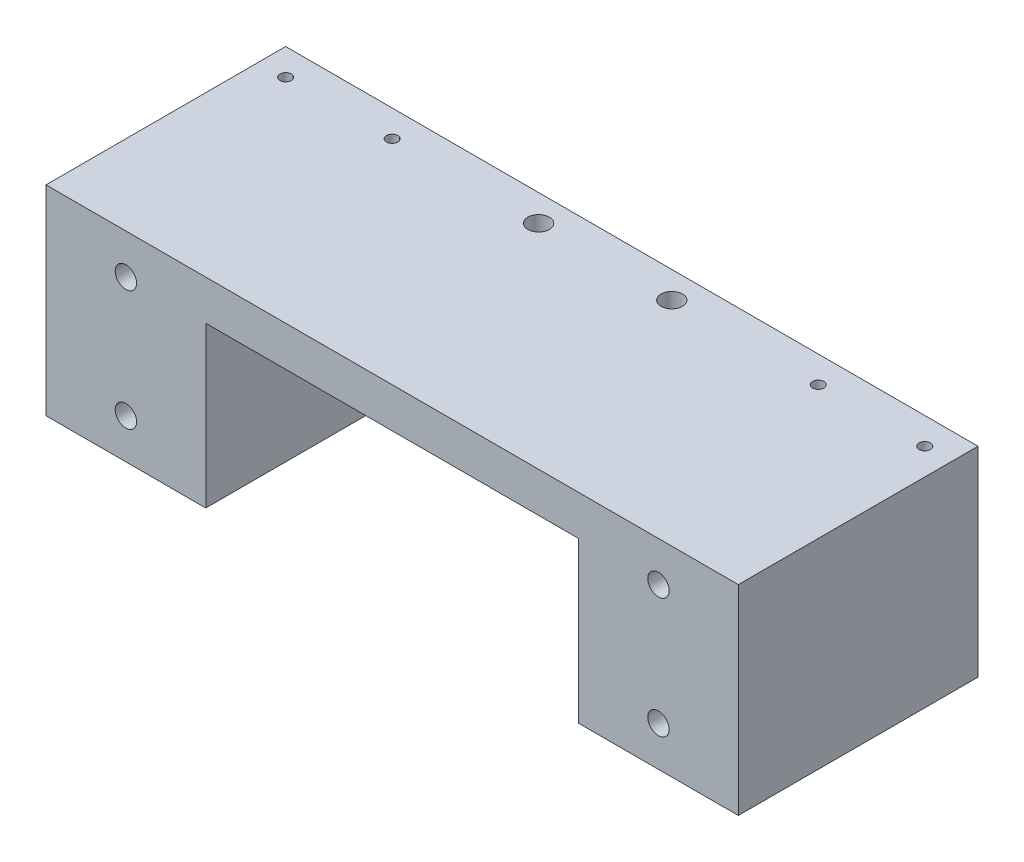
SolidWorks part; units mm, degrees
material "6061 Alloy"
ref_plane "Front Plane" through (0, 0, 0) normal (0, 0, 1) x (1, 0, 0)
ref_plane "Top Plane" through (0, 0, 0) normal (0, 1, 0) x (1, 0, 0)
ref_plane "Right Plane" through (0, 0, 0) normal (1, 0, 0) x (0, 0, -1)
sketch "Sketch1" plane through (0, 0, 0) normal (0, 0, 1) x (1, 0, 0)
  line L1 (-82.55, -114.3) -> (82.55, -114.3)
  line L2 (-82.55, -114.3) -> (-82.55, 114.3)
  line L3 (-82.55, 114.3) -> (82.55, 114.3)
  line L4 (82.55, -114.3) -> (82.55, 114.3)
  line L5 (-82.55, -114.3) -> (82.55, 114.3) construction
  line L6 (-82.55, 114.3) -> (82.55, -114.3) construction
  point P0 (0, 0)
  dimension "D1" = 228.6
  dimension "D2" = 165.1
extrude "Boss-Extrude1" add sketch "Sketch1" along normal blind 19.05
sketch "Sketch2" plane through (0, 0, 19.05) normal (0, 0, 1) x (1, 0, 0)
  line L0 (-82.55, -114.3) -> (82.55, -114.3) construction
  line L1 (-38.1, -114.3) -> (38.1, -114.3)
  line L2 (-38.1, -114.3) -> (-38.1, 88.9)
  line L3 (-38.1, 88.9) -> (38.1, 88.9)
  line L4 (38.1, -114.3) -> (38.1, 88.9)
  line L5 (-82.55, 114.3) -> (-82.55, -114.3) construction
  dimension "D1" = 203.2
  dimension "D2" = 76.2
  dimension "D3" = 44.45
extrude "Cut-Extrude1" cut sketch "Sketch2" against normal through all
sketch "Sketch3" plane through (0, 0, 0) normal (0, 0, -1) x (-1, 0, 0)
  line L0 (82.55, 114.3) -> (82.55, -114.3) construction
  line L1 (-82.55, 114.3) -> (82.55, 114.3)
  line L2 (-82.55, 114.3) -> (-82.55, 104.775)
  line L3 (-82.55, 104.775) -> (82.55, 104.775)
  line L4 (82.55, 114.3) -> (82.55, 104.775)
  dimension "D1" = 9.525
extrude "Boss-Extrude2" add sketch "Sketch3" along normal blind 57.15
sketch "Sketch4" plane through (0, 0, -57.15) normal (0, 0, -1) x (-1, 0, 0)
  line L7 (-82.55, 104.775) -> (-63.5, 104.775)
  line L8 (-82.55, 104.775) -> (-82.55, 66.675)
  line L9 (-82.55, 66.675) -> (-63.5, 66.675)
  line L10 (-63.5, 104.775) -> (-63.5, 66.675)
  dimension "D1" = 38.1
  dimension "D2" = 19.05
extrude "Boss-Extrude3" add sketch "Sketch4" against normal blind 12.7
mirror "Mirror1" about plane through (0, 0, 0) normal (1, 0, 0) of "Boss-Extrude3"
sketch "Sketch7" plane through (0, 0, 19.05) normal (0, 0, 1) x (1, 0, 0)
  line L0 (-82.55, -114.3) -> (-38.1, -114.3) construction
  line L1 (-104.775, -101.6) -> (-15.875, -101.6)
  line L2 (-104.775, -101.6) -> (-104.775, -114.3)
  line L3 (-104.775, -114.3) -> (-15.875, -114.3)
  line L4 (-15.875, -101.6) -> (-15.875, -114.3)
  line L5 (-104.775, -101.6) -> (-15.875, -114.3) construction
  line L6 (-104.775, -114.3) -> (-15.875, -101.6) construction
  line L7 (-82.55, 114.3) -> (-82.55, -114.3) construction
  point P0 (-60.325, -107.95)
  dimension "D1" = 0
  dimension "D2" = 88.9
  dimension "D3" = 22.225
  dimension "D4" = 12.7
extrude "Boss-Extrude4" add sketch "Sketch7" against normal blind 19.05
sketch "Sketch8" plane through (0, -114.3, 0) normal (0, -1, 0) x (-1, 0, 0)
  line L0 (104.775, -19.05) -> (15.875, -19.05) construction
  line L1 (101.6, 0) -> (19.05, 0)
  line L2 (101.6, 0) -> (101.6, -19.05)
  line L3 (101.6, -19.05) -> (19.05, -19.05)
  line L4 (19.05, 0) -> (19.05, -19.05)
  line L5 (101.6, 0) -> (19.05, -19.05) construction
  line L6 (101.6, -19.05) -> (19.05, 0) construction
  line L8 (104.775, 0) -> (104.775, -19.05) construction
  line L9 (15.875, 0) -> (15.875, -19.05) construction
  point P0 (60.325, -9.525)
  dimension "D1" = 19.05
  dimension "D2" = 3.175
  dimension "D3" = 3.175
extrude "Cut-Extrude4" cut sketch "Sketch8" against normal blind 2.54
mirror "Mirror3" about plane through (0, 0, 0) normal (1, 0, 0) of "Cut-Extrude4", "Boss-Extrude4"
hole_wizard "#8-32 Tapped Hole1" positions "Sketch11" profile "Sketch10" tap size "#8-32" standard "ANSI Inch"
sketch "Sketch11" plane through (0, 114.3, 0) normal (0, 1, 0) x (1, 0, 0)
  line L0 (-82.55, 0) -> (-82.55, -19.05) construction
  line L1 (-82.55, -19.05) -> (-82.55, 57.15) construction
  line L2 (82.55, 0) -> (82.55, -19.05) construction
  line L3 (82.55, -19.05) -> (82.55, 57.15) construction
  line L4 (82.55, -19.05) -> (-82.55, -19.05) construction
  point P0 (-76.2, -12.7)
  point P2 (-63.5, -12.7)
  point P4 (63.5, -12.7)
  point P6 (76.2, -12.7)
  dimension "D1" = 6.35
  dimension "D2" = 19.05
  dimension "D3" = 6.35
  dimension "D4" = 19.05
  dimension "D5" = 6.35
  dimension "D6" = 6.35
  dimension "D7" = 6.35
  dimension "D8" = 6.35
cosmetic thread "Hole Thread1" parameters "D1"=3.048, "D2"=4.1656
cosmetic thread "Hole Thread2" parameters "D1"=3.048, "D2"=4.1656
cosmetic thread "Hole Thread3" parameters "D1"=3.048, "D2"=4.1656
cosmetic thread "Hole Thread4" parameters "D1"=3.048, "D2"=4.1656
sketch "Sketch10" plane through (-76.2, 114.3, 12.7) normal (1, 0, 0) x (0, 0, 1)
  line L0 (0, 0) -> (0, 13.7378)
  line L1 (0, 13.7378) -> (1.7272, 12.7)
  line L2 (1.7272, 12.7) -> (1.7272, 0)
  line L5 (1.7272, 0) -> (0, 0)
  line L10 (0, 13.7378) -> (-1.7272, 12.7) construction
  line L11 (0, -6.35) -> (0, 107.95) construction
  dimension "Tap Drill Dia." = 3.4544
  dimension "Tap Drill Depth" = 12.7
  dimension "Drill Angle" = 118
hole_wizard "1/4 Clearance Hole1" positions "Sketch12" profile "Sketch13" hole size "1/4" standard "ANSI Inch"
sketch "Sketch12" plane through (0, -101.6, 0) normal (0, 1, 0) x (1, 0, 0)
  line L0 (-104.775, 0) -> (-104.775, -19.05) construction
  line L1 (-82.55, 0) -> (-104.775, 0) construction
  line L2 (-15.875, 0) -> (-38.1, 0) construction
  line L3 (-15.875, 0) -> (-15.875, -19.05) construction
  line L4 (15.875, 0) -> (15.875, -19.05) construction
  line L5 (15.875, 0) -> (38.1, 0) construction
  line L6 (82.55, 0) -> (104.775, 0) construction
  line L7 (104.775, 0) -> (104.775, -19.05) construction
  point P0 (-95.25, -6.35)
  point P2 (-25.4, -6.35)
  point P4 (25.4, -6.35)
  point P6 (95.25, -6.35)
  dimension "D1" = 9.525
  dimension "D2" = 6.35
  dimension "D3" = 6.35
  dimension "D4" = 9.525
  dimension "D5" = 9.525
  dimension "D6" = 6.35
  dimension "D7" = 6.35
  dimension "D8" = 9.525
sketch "Sketch13" plane through (-95.25, -101.6, 6.35) normal (1, 0, 0) x (0, 0, 1)
  line L0 (0, 0) -> (0, 10.16)
  line L1 (0, 10.16) -> (3.3782, 10.16)
  line L2 (3.3782, 10.16) -> (3.3782, 0)
  line L5 (3.3782, 0) -> (0, 0)
  line L11 (0, -6.35) -> (0, 107.95) construction
  dimension "Thru Hole Dia." = 6.7564
  dimension "Thru Hole Depth" = 10.16
hole_wizard "CBORE for #8 Socket Head Cap Screw1" positions "Sketch18" profile "Sketch19" counterbore size "#8" standard "ANSI Inch" end condition up to next
sketch "Sketch18" plane through (0, 0, 19.05) normal (0, 0, 1) x (1, 0, 0)
  line L0 (-82.55, 114.3) -> (-82.55, -101.6) construction
  line L1 (-38.1, 88.9) -> (-38.1, -101.6) construction
  line L2 (38.1, -101.6) -> (38.1, 88.9) construction
  line L3 (82.55, -101.6) -> (82.55, 114.3) construction
  point P0 (-76.2, 9.525)
  point P2 (-44.45, 9.525)
  point P4 (44.45, 9.525)
  point P6 (76.2, 9.525)
  dimension "D1" = 6.35
  dimension "D2" = 6.35
  dimension "D3" = 6.35
  dimension "D4" = 6.35
  dimension "D5" = 111.125
  dimension "D6" = 111.125
  dimension "D7" = 111.125
  dimension "D8" = 111.125
sketch "Sketch19" plane through (-76.2, 9.525, 19.05) normal (1, 0, 0) x (0, -1, 0)
  line L0 (0, 0) -> (0, 19.05)
  line L1 (0, 19.05) -> (2.2479, 19.05)
  line L3 (2.2479, 19.05) -> (2.2479, 4.1656)
  line L4 (2.2479, 4.1656) -> (3.9687, 4.1656)
  line L5 (3.9687, 4.1656) -> (3.9687, 0)
  line L7 (3.9687, 0) -> (0, 0)
  line L11 (0, -6.35) -> (0, 107.95) construction
  dimension "Thru Hole Dia." = 4.4958
  dimension "Thru Hole Depth" = 19.05
  dimension "C'Bore Dia." = 7.9375
  dimension "C'Bore Depth" = 4.1656
hole_wizard "1/4-20 Tapped Hole1" positions "Sketch20" profile "Sketch21" tap size "1/4-20" standard "ANSI Inch" end condition through all
sketch "Sketch20" plane through (0, 114.3, 0) normal (0, 1, 0) x (1, 0, 0)
  line L0 (-82.55, -19.05) -> (-82.55, 57.15) construction
  line L1 (82.55, -19.05) -> (82.55, 57.15) construction
  line L2 (-82.55, 57.15) -> (82.55, 57.15) construction
  point P0 (15.875, 50.8)
  point P2 (-15.875, 50.8)
  dimension "D1" = 66.675
  dimension "D2" = 66.675
  dimension "D3" = 6.35
  dimension "D4" = 6.35
cosmetic thread "Hole Thread5" parameters "D2"=6.35
cosmetic thread "Hole Thread6" parameters "D2"=6.35
sketch "Sketch21" plane through (15.875, 114.3, -50.8) normal (1, 0, 0) x (0, 0, 1)
  line L0 (0, 0) -> (0, 228.6)
  line L1 (0, 228.6) -> (2.5527, 228.6)
  line L2 (2.5527, 228.6) -> (2.5527, 0)
  line L5 (2.5527, 0) -> (0, 0)
  line L11 (0, -6.35) -> (0, 107.95) construction
  dimension "Thru Tap Drill Dia." = 5.1054
  dimension "Thru Tap Drill Depth" = 228.6
sketch "Sketch22" plane through (0, 0, -57.15) normal (0, 0, -1) x (-1, 0, 0)
  line L0 (-63.5, 104.775) -> (63.5, 104.775) construction
  line L1 (3.175, 98.425) -> (-3.175, 98.425)
  line L2 (3.175, 98.425) -> (3.175, 104.775)
  line L3 (3.175, 104.775) -> (-3.175, 104.775)
  line L4 (-3.175, 98.425) -> (-3.175, 104.775)
  line L5 (3.175, 98.425) -> (-3.175, 104.775) construction
  line L6 (3.175, 104.775) -> (-3.175, 98.425) construction
  point P0 (0, 101.6)
  dimension "D1" = 6.35
  dimension "D2" = 6.35
  dimension "D3" = 0
extrude "Boss-Extrude5" add sketch "Sketch22" along normal blind 3.175 from offset 7.9375 separate body offset against normal yes
sketch "Sketch23" plane through (0, 0, -52.3875) normal (0, 0, -1) x (-1, 0, 0)
  line L0 (-3.175, 98.425) -> (3.175, 98.425) construction
  line L1 (-3.175, 104.775) -> (-3.175, 98.425) construction
  circle A0 centre (0, 101.6) radius 1.5875
  dimension "D3" = 3.175
  dimension "D1" = 3.175
  dimension "D2" = 3.175
extrude "Cut-Extrude5" cut sketch "Sketch23" against normal up to next (3.175 mm away)
sketch "Sketch27" plane through (82.55, 0, 0) normal (1, 0, 0) x (0, 0, -1)
  line L6 (57.15, 114.3) -> (0, 114.3)
  line L7 (57.15, 114.3) -> (57.15, 66.6142)
  line L8 (57.15, 66.6142) -> (0, 66.6142)
  line L9 (0, 114.3) -> (0, 66.6142)
extrude "Boss-Extrude6" add sketch "Sketch27" against normal blind 38.1
mirror "Mirror4" about plane through (0, 0, 0) normal (1, 0, 0) of "Boss-Extrude6"
sketch "Sketch26" plane through (104.775, 0, 0) normal (1, 0, 0) x (0, 0, -1)
  line L0 (-19.05, 114.3) -> (57.15, 114.3) construction
  line L1 (-19.05, -114.3) -> (0, -114.3)
  line L2 (-19.05, -114.3) -> (-19.05, 114.3)
  line L3 (-19.05, 114.3) -> (0, 114.3)
  line L4 (0, -114.3) -> (0, 114.3)
extrude "Cut-Extrude7" cut sketch "Sketch26" against normal through all
hole_wizard "#6-32 Tapped Hole1" positions "Sketch28" profile "Sketch29" tap size "#6-32" standard "ANSI Inch" end condition through all
sketch "Sketch28" plane through (0, 114.3, 0) normal (0, 1, 0) x (1, 0, 0)
  line L0 (-82.55, 0) -> (-82.55, 57.15) construction
  line L1 (-82.55, 57.15) -> (82.55, 57.15) construction
  line L2 (82.55, 0) -> (82.55, 57.15) construction
  point P0 (-76.2, 50.8)
  point P2 (-50.8, 50.8)
  point P4 (50.8, 50.8)
  point P6 (76.2, 50.8)
  dimension "D1" = 6.35
  dimension "D2" = 25.4
  dimension "D3" = 6.35
  dimension "D4" = 6.35
  dimension "D5" = 6.35
  dimension "D6" = 6.35
  dimension "D7" = 25.4
  dimension "D8" = 6.35
sketch "Sketch29" plane through (-76.2, 114.3, -50.8) normal (1, 0, 0) x (0, 0, 1)
  line L0 (0, 0) -> (0, 47.6858)
  line L1 (0, 47.6858) -> (1.3525, 47.6858)
  line L2 (1.3525, 47.6858) -> (1.3525, 0)
  line L5 (1.3525, 0) -> (0, 0)
  line L11 (0, -6.35) -> (0, 107.95) construction
  dimension "Thru Tap Drill Dia." = 2.7051
  dimension "Thru Tap Drill Depth" = 47.6858
cosmetic thread "Hole Thread7" parameters "D2"=3.5052
cosmetic thread "Hole Thread8" parameters "D2"=3.5052
cosmetic thread "Hole Thread9" parameters "D2"=3.5052
cosmetic thread "Hole Thread10" parameters "D2"=3.5052
hole_wizard "1/4-20 Tapped Hole2" positions "Sketch30" profile "Sketch31" tap size "1/4-20" standard "ANSI Inch" end condition through all
sketch "Sketch30" plane through (0, 0, 0) normal (0, 0, 1) x (1, 0, 0)
  line L0 (-82.55, 66.6142) -> (-82.55, 114.3) construction
  line L1 (44.45, 104.775) -> (44.45, 66.6142) construction
  line L2 (-44.45, 66.6142) -> (-82.55, 66.6142) construction
  line L3 (-82.55, 114.3) -> (82.55, 114.3) construction
  line L4 (44.45, 66.6142) -> (82.55, 66.6142) construction
  point P0 (-63.5, 104.775)
  point P2 (-63.5, 76.1392)
  point P4 (63.5, 104.775)
  point P6 (63.5, 76.1392)
  dimension "D1" = 19.05
  dimension "D2" = 19.05
  dimension "D3" = 19.05
  dimension "D4" = 19.05
  dimension "D5" = 9.525
  dimension "D6" = 9.525
  dimension "D7" = 9.525
  dimension "D8" = 9.525
sketch "Sketch31" plane through (-63.5, 104.775, 0) normal (1, 0, 0) x (0, -1, 0)
  line L0 (0, 0) -> (0, 57.15)
  line L1 (0, 57.15) -> (2.5527, 57.15)
  line L2 (2.5527, 57.15) -> (2.5527, 0)
  line L5 (2.5527, 0) -> (0, 0)
  line L11 (0, -6.35) -> (0, 107.95) construction
  dimension "Thru Tap Drill Dia." = 5.1054
  dimension "Thru Tap Drill Depth" = 57.15
cosmetic thread "Hole Thread11" parameters "D2"=6.35
cosmetic thread "Hole Thread12" parameters "D2"=6.35
cosmetic thread "Hole Thread13" parameters "D2"=6.35
cosmetic thread "Hole Thread14" parameters "D2"=6.35
